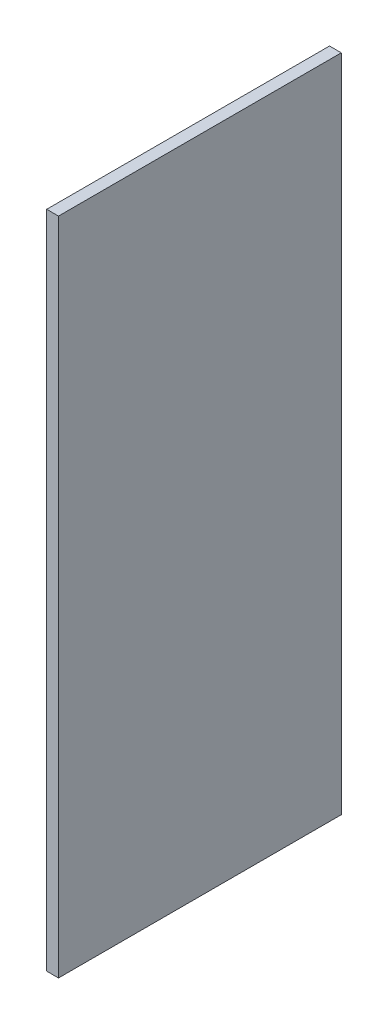
SolidWorks part; units mm, degrees
ref_plane "Ebene vorne" through (0, 0, 0) normal (0, 0, 1) x (1, 0, 0)
ref_plane "Ebene oben" through (0, 0, 0) normal (0, 1, 0) x (1, 0, 0)
ref_plane "Ebene rechts" through (0, 0, 0) normal (1, 0, 0) x (0, 0, -1)
sketch "Skizze1" plane through (0, 0, 0) normal (1, 0, 0) x (0, 0, -1)
  line L1 (-60, 140) -> (60, 140)
  line L2 (-60, 140) -> (-60, -140)
  line L3 (-60, -140) -> (60, -140)
  line L4 (60, 140) -> (60, -140)
  line L5 (-60, 140) -> (60, -140) construction
  line L6 (-60, -140) -> (60, 140) construction
  point P0 (0, 0)
  dimension "D1" = 120
  dimension "D2" = 280
extrude "Aufsatz-Linear austragen1" add sketch "Skizze1" along normal blind 5
